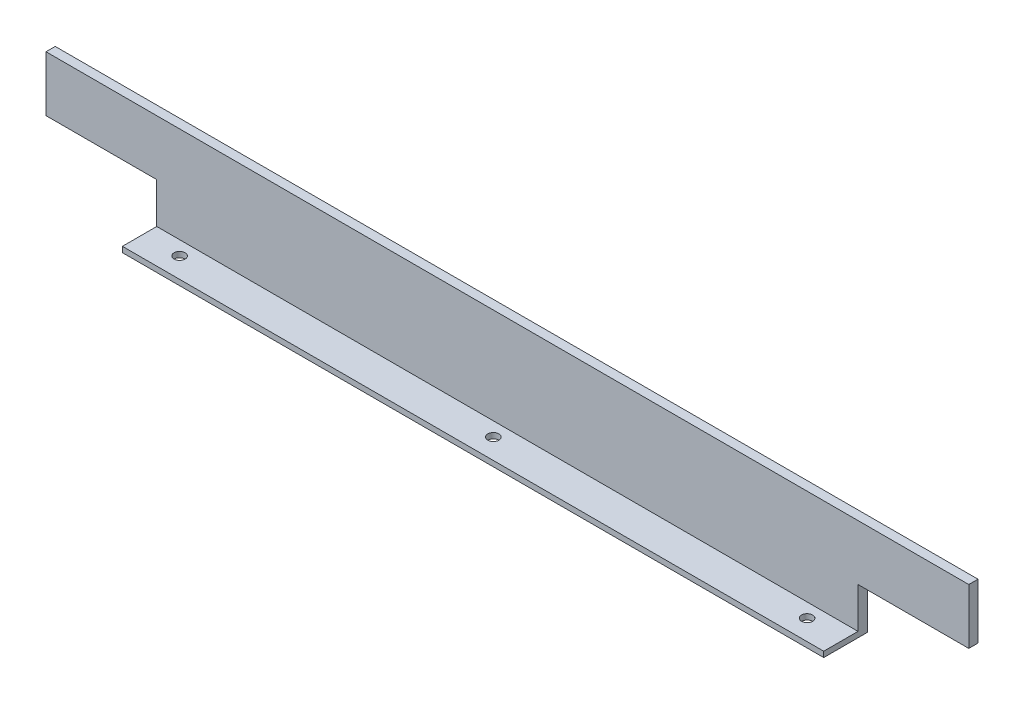
SolidWorks part; units mm, degrees
material "锻制不锈钢"
ref_plane "前视基准面" through (0, 0, 0) normal (0, 0, 1) x (1, 0, 0)
ref_plane "上视基准面" through (0, 0, 0) normal (0, 1, 0) x (1, 0, 0)
ref_plane "右视基准面" through (0, 0, 0) normal (1, 0, 0) x (0, 0, -1)
other "Configuration Table"
sketch "草图1" plane through (0, 0, 0) normal (0, 0, 1) x (1, 0, 0)
  line L1 (-167.2956, 147.9193) -> (332.7044, 147.9193)
  line L2 (-167.2956, 147.9193) -> (-167.2956, 92.9193)
  line L3 (-167.2956, 92.9193) -> (332.7044, 92.9193)
  line L4 (332.7044, 147.9193) -> (332.7044, 92.9193)
  dimension "D1" = 500
  dimension "D2" = 55
extrude "凸台-拉伸1" add sketch "草图1" along normal blind 5
sketch "草图2" plane through (0, 0, 0) normal (0, 0, -1) x (-1, 0, 0)
  line L0 (-332.7044, 92.9193) -> (-332.7044, 147.9193) construction
  line L1 (-332.7044, 117.9193) -> (167.2956, 117.9193)
  line L2 (-332.7044, 117.9193) -> (-332.7044, 112.9193)
  line L3 (-332.7044, 112.9193) -> (167.2956, 112.9193)
  line L4 (167.2956, 117.9193) -> (167.2956, 112.9193)
  line L5 (-332.7044, 147.9193) -> (167.2956, 147.9193) construction
  dimension "D1" = 5
  dimension "D2" = 30
extrude "凸台-拉伸2" add sketch "草图2" along normal blind 10
sketch "草图3" plane through (332.7044, 0, 0) normal (1, 0, 0) x (0, 0, -1)
  line L0 (-69.1955, 186.6335) -> (-39.7721, 186.6335)
  line L1 (-39.7721, 186.6335) -> (-23.6, 179.6485)
  line L2 (-23.6, 179.6485) -> (-23.6, 92.9193)
  line L3 (-23.6, 92.9193) -> (-5, 92.9193)
  line L4 (-69.1955, 186.6335) -> (-85.6, 179.6485)
  line L5 (-85.6, 179.6485) -> (-85.6, 81.6485)
  line L6 (-85.6, 81.6485) -> (-23.6, 81.6485)
  line L7 (-23.6, 81.6485) -> (-23.6, 92.9193)
  dimension "D1" = 62
  dimension "D2" = 18.6
  dimension "D3" = 98
sketch "草图6" plane through (0, 0, 5) normal (0, 0, 1) x (1, 0, 0)
  line L0 (-167.2956, 117.9193) -> (332.7044, 117.9193) construction
  line L1 (332.7044, 92.9193) -> (272.7044, 92.9193)
  line L2 (332.7044, 92.9193) -> (332.7044, 117.9193)
  line L3 (332.7044, 117.9193) -> (272.7044, 117.9193)
  line L4 (272.7044, 92.9193) -> (272.7044, 117.9193)
  line L5 (-167.2956, 92.9193) -> (-107.2956, 92.9193)
  line L6 (-167.2956, 92.9193) -> (-167.2956, 117.9193)
  line L7 (-167.2956, 117.9193) -> (-107.2956, 117.9193)
  line L8 (-107.2956, 92.9193) -> (-107.2956, 117.9193)
  dimension "D1" = 60
  dimension "D2" = 60
extrude "切除-拉伸2" cut sketch "草图6" against normal through all
sketch "草图7" plane through (272.7044, 0, 0) normal (1, 0, 0) x (0, 0, -1)
  line L1 (-5, 92.9193) -> (-23.6, 92.9193)
  line L2 (-5, 92.9193) -> (-5, 95.9193)
  line L3 (-5, 95.9193) -> (-23.6, 95.9193)
  line L4 (-23.6, 92.9193) -> (-23.6, 95.9193)
  dimension "D1" = 18.6
  dimension "D2" = 3
extrude "凸台-拉伸5" add sketch "草图7" against normal blind 380
sketch "草图8" plane through (0, 95.9193, 0) normal (0, 1, 0) x (1, 0, 0)
  line L1 (-107.2956, -5) -> (-107.2956, -23.6) construction
  line L3 (-107.2956, -23.6) -> (272.7044, -23.6) construction
  circle A0 centre (-87.2956, -12.6) radius 3
  circle A1 centre (82.7044, -12.6) radius 3
  circle A2 centre (252.7044, -12.6) radius 3
  dimension "D1" = 6
  dimension "D2" = 6
  dimension "D3" = 6
  dimension "D4" = 170
  dimension "D5" = 170
  dimension "D6" = 20
  dimension "1" = 11
extrude "切除-拉伸3" cut sketch "草图8" against normal through all
